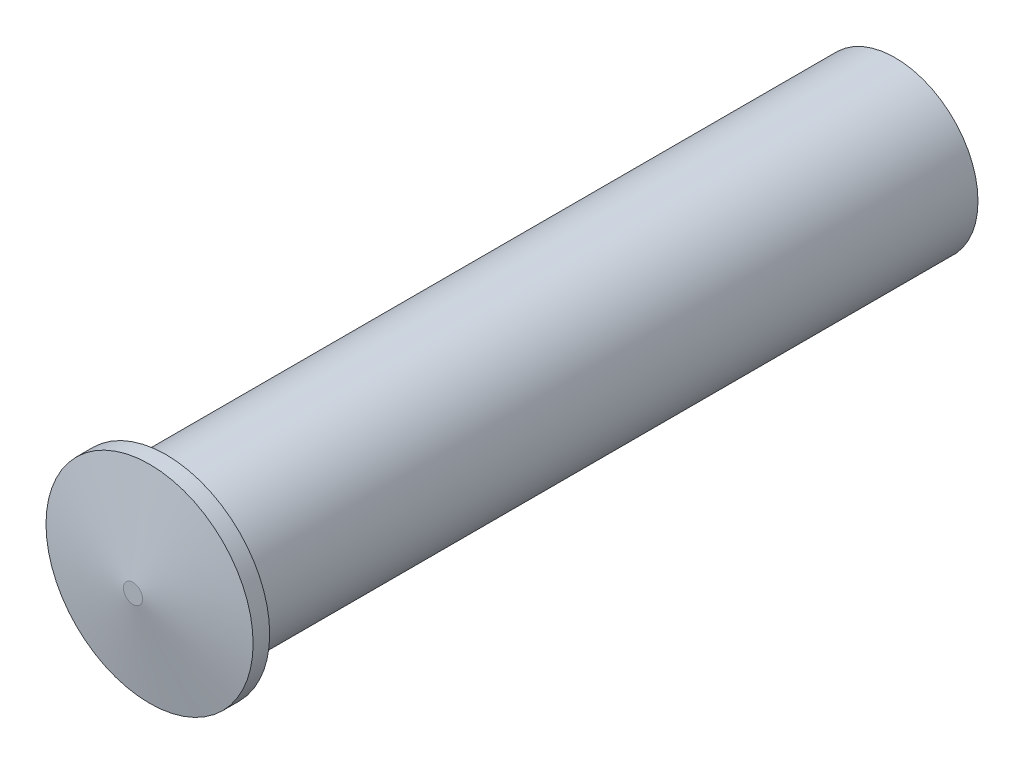
SolidWorks part; units mm, degrees
ref_plane "Front Plane" through (0, 0, 0) normal (0, 0, 1) x (1, 0, 0)
ref_plane "Top Plane" through (0, 0, 0) normal (0, 1, 0) x (1, 0, 0)
ref_plane "Right Plane" through (0, 0, 0) normal (1, 0, 0) x (0, 0, -1)
sketch "Sketch1" plane through (0, 0, 0) normal (0, 0, 1) x (1, 0, 0)
  line L0 (0, -44.5788) -> (0, 47.9169) construction
  line L1 (53.8578, 0) -> (-57.3712, 0) construction
  circle A0 centre (0, 0) radius 10
sketch "Sketch2" plane through (0, 0, 0) normal (0, 1, 0) x (1, 0, 0)
  line L0 (0, 172.8456) -> (0, -46.9914) construction
extrude "Boss-Extrude2" add sketch "Sketch1" against normal blind 88
sketch "Sketch5" plane through (0, 0, 0) normal (0, 0, 1) x (1, 0, 0)
  circle A0 centre (0, 0) radius 12.5
extrude "Boss-Extrude3" add sketch "Sketch5" along normal blind 2
sketch "Sketch6" plane through (0, 0, 2) normal (0, 0, 1) x (1, 0, 0)
  circle A1 centre (0, 0) radius 12.5
extrude "Boss-Extrude4" add sketch "Sketch6" along normal blind 2 draft 80
sketch "Sketch7" plane through (0, 0, -88) normal (0, 0, -1) x (-1, 0, 0)
  circle A0 centre (0, 0) radius 8
extrude "Cut-Extrude1" cut sketch "Sketch7" against normal blind 88
